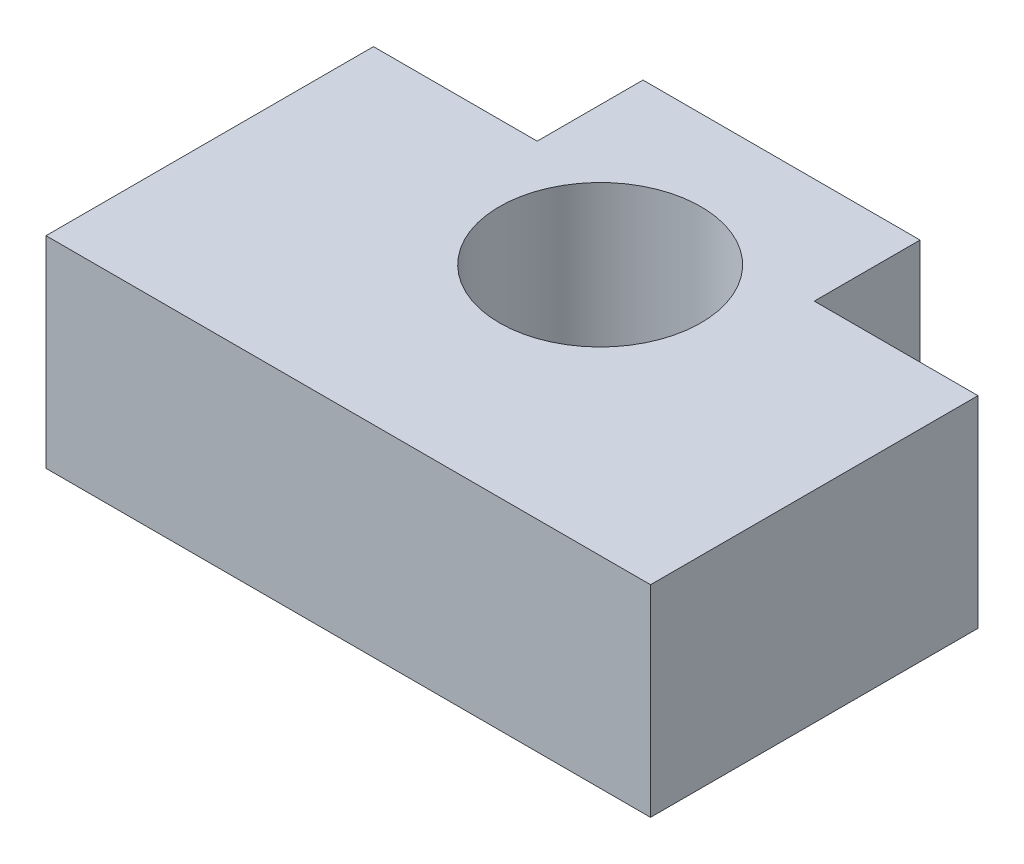
SolidWorks part; units mm, degrees
material "Chrome Stainless Steel"
ref_plane "Front Plane" through (0, 0, 0) normal (0, 0, 1) x (1, 0, 0)
ref_plane "Top Plane" through (0, 0, 0) normal (0, 1, 0) x (1, 0, 0)
ref_plane "Right Plane" through (0, 0, 0) normal (1, 0, 0) x (0, 0, -1)
sketch "Sketch1" plane through (0, 0, 0) normal (0, 1, 0) x (1, 0, 0)
  line L0 (30, 43) -> (30, -0.4221) construction
  line L5 (0, 32.5) -> (0, 0)
  line L8 (60, 32.5) -> (43.75, 32.5)
  line L9 (43.75, 43) -> (43.75, 32.5)
  line L12 (0, 32.5) -> (16.25, 32.5)
  line L13 (16.25, 43) -> (16.25, 32.5)
  line L14 (60, 0) -> (60, 32.5)
  line L15 (60, 0) -> (0, 0)
  line L16 (16.25, 43) -> (43.75, 43)
  point P11 (43.75, 37.75)
  dimension "D4" = 27.5
extrude "Boss-Extrude1" add sketch "Sketch1" along normal blind 20
sketch "Sketch2" plane through (0, 20, 0) normal (0, 1, 0) x (1, 0, 0)
  line L0 (30, 43) -> (30, 0) construction
  line L1 (43.75, 43) -> (16.25, 43) construction
  line L2 (0, 0) -> (60, 0) construction
  line L3 (0, 25) -> (60, 25) construction
  line L4 (0, 32.5) -> (0, 0) construction
  line L5 (60, 0) -> (60, 32.5) construction
  circle A0 centre (30, 25) radius 10
  dimension "D1" = 25
extrude "Cut-Extrude1" cut sketch "Sketch2" against normal through all
sketch "Sketch4" plane through (0, 20, 0) normal (0, 1, 0) x (1, 0, 0)
  line L0 (30, 43) -> (30, 0) construction
  line L1 (43.75, 43) -> (16.25, 43) construction
  line L2 (0, 0) -> (60, 0) construction
  line L3 (20, 25) -> (60, 25) construction
  line L4 (60, 0) -> (60, 32.5) construction
  circle A0 centre (30, 25) radius 10 construction
  circle A1 centre (30, 25) radius 9
  circle A2 centre (30, 25) radius 5
